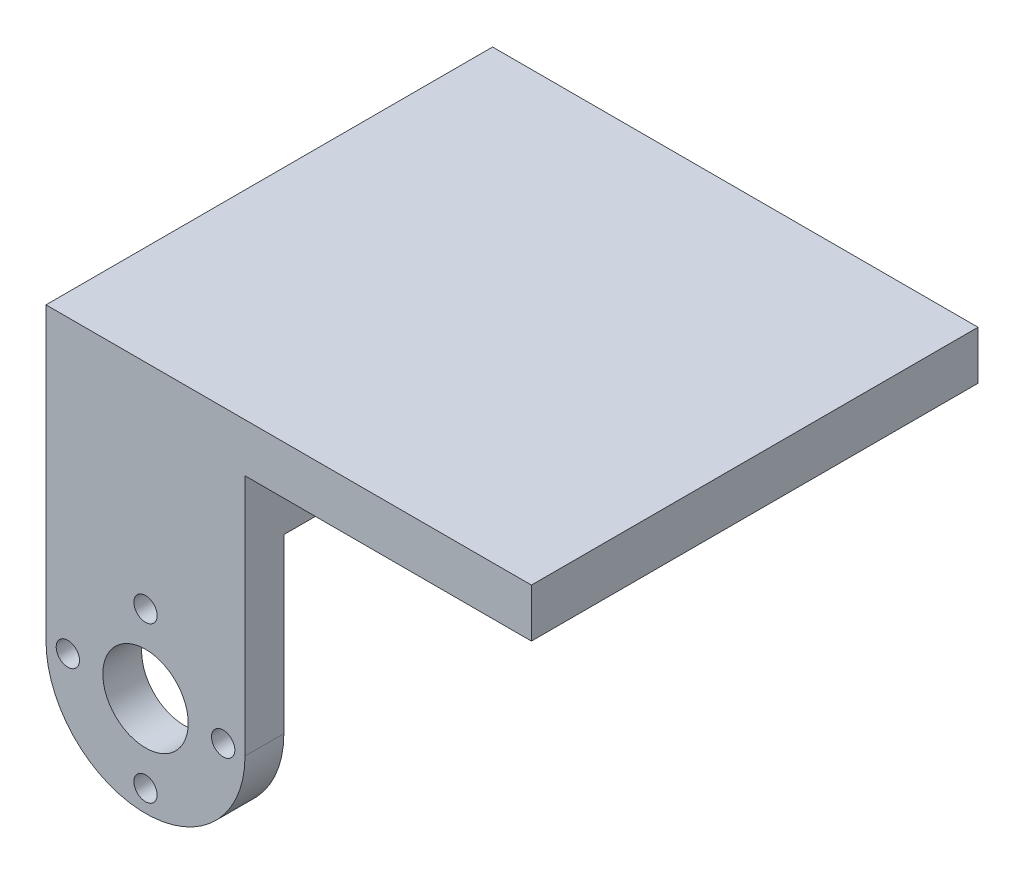
SolidWorks part; units mm, degrees
ref_plane "Front Plane" through (0, 0, 0) normal (0, 0, 1) x (1, 0, 0)
ref_plane "Top Plane" through (0, 0, 0) normal (0, 1, 0) x (1, 0, 0)
ref_plane "Right Plane" through (0, 0, 0) normal (1, 0, 0) x (0, 0, -1)
sketch "Sketch1" plane through (0, 0, 0) normal (0, 0, 1) x (1, 0, 0)
  line L2 (10.25, 0) -> (-10.25, 0)
  line L3 (10.25, 0) -> (10.25, 25)
  line L6 (10.25, 25) -> (-10.25, 25)
  line L9 (-10.25, 0) -> (-10.25, 25)
  line L10 (-10.25, 25) -> (39.75, 25)
  line L11 (-10.25, 25) -> (-10.25, 30)
  line L12 (-10.25, 30) -> (39.75, 30)
  line L13 (39.75, 25) -> (39.75, 30)
  circle A0 centre (0, 0) radius 10.25
  circle A5 centre (0, 0) radius 4.4
  circle A6 centre (0, 0) radius 8
  circle A7 centre (0, 8) radius 1.2
  circle A8 centre (8, 0) radius 1.2
  circle A9 centre (0, -8) radius 1.2
  circle A10 centre (-8, 0) radius 1.2
  point P36 (0, 0)
  dimension "D1" = 25
  dimension "D4" = 5
  dimension "D7" = 8.8
  dimension "D8" = 2.4
  dimension "D3" = 50
  dimension "D9" = 4
extrude "Boss-Extrude1" add sketch "Sketch1" against normal blind 46 contours A0 L3 L6 L9 | A10 A6 A7 A8 L2 A0 | A10 L2 A5 A8 A6 A7 | A10 L2 A0 A8 A6 A9 | A10 A6 A9 A8 L2 A5 | L11 L12 L13 L10
sketch "Sketch2" plane through (-10.25, 0, 0) normal (-1, 0, 0) x (0, 0, 1)
  line L0 (-46, -10.25) -> (0, -10.25) construction
  line L1 (-4, -10.25) -> (-42, -10.25)
  line L2 (-4, -10.25) -> (-4, 17.75)
  line L3 (-4, 17.75) -> (-42, 17.75)
  line L4 (-42, -10.25) -> (-42, 17.75)
  line L5 (-46, 0) -> (-46, 30) construction
  line L6 (0, -10.25) -> (0, 0) construction
  dimension "D1" = 4
  dimension "D2" = 4
  dimension "D3" = 28
extrude "Cut-Extrude1" cut sketch "Sketch2" against normal blind 46
